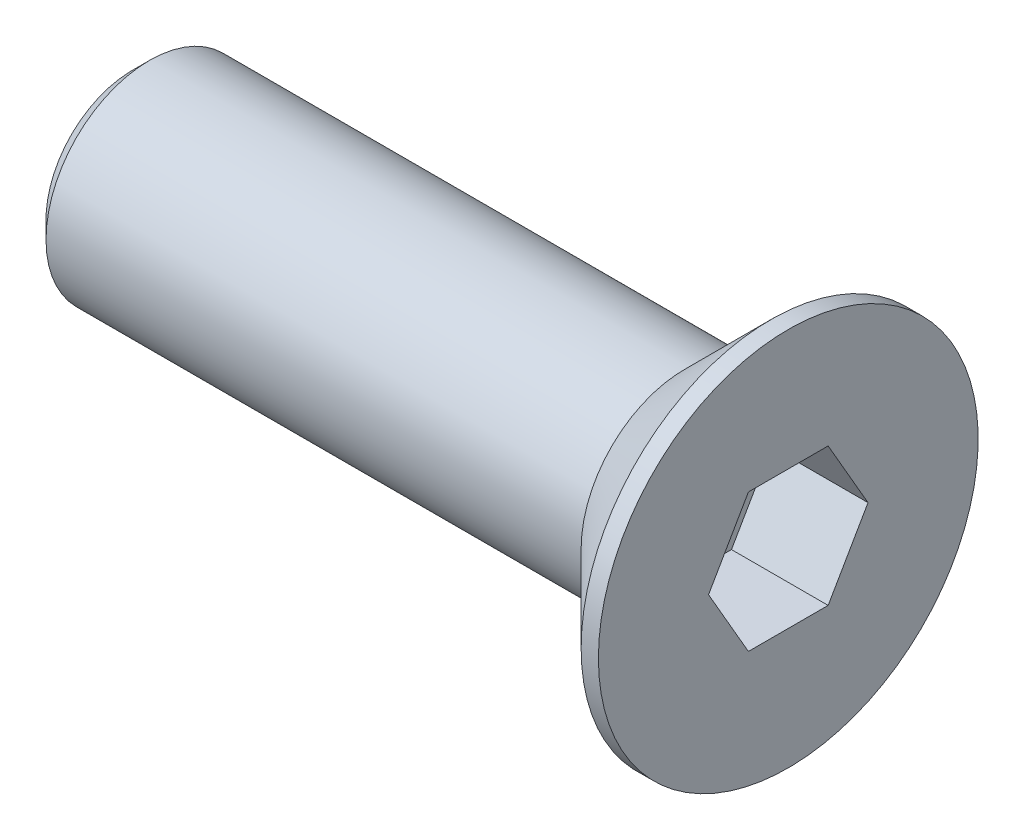
SolidWorks part; units mm, degrees
ref_plane "Plan1" through (0, 0, 0) normal (0, 0, 1) x (1, 0, 0)
ref_plane "Plan2" through (0, 0, 0) normal (0, 1, 0) x (1, 0, 0)
ref_plane "Plan3" through (0, 0, 0) normal (1, 0, 0) x (0, 0, -1)
sketch "Esquisse1" plane through (0, 0, 0) normal (0, 0, 1) x (1, 0, 0)
  line L0 (-25.8285, 0) -> (47.3208, 0) construction
  line L1 (0, 0) -> (0, 3)
  line L2 (0, 3) -> (16, 3)
  line L3 (16, 3) -> (18.5, 5.5)
  line L4 (19, 5.5) -> (19, 0)
  line L5 (19, 0) -> (0, 0)
  line L6 (18.5, 5.5) -> (19, 5.5)
  dimension "D1" = 6
  dimension "D2" = 16
  dimension "D3" = 45
  dimension "D4" = 11
  dimension "D5" = 3
revolve "Base-Révolution" add sketch "Esquisse1" angle 360 about L0
chamfer "Chanfrein2" distance 0.5 angle 45 1 edges at (0, 0, 3)
sketch "Esquisse2" plane through (19, 0, 0) normal (1, 0, 0) x (0, 0, -1)
  line L1 (2.3094, 0) -> (1.1547, 2)
  line L2 (1.1547, 2) -> (-1.1547, 2)
  line L3 (-1.1547, 2) -> (-2.3094, 0)
  line L4 (-2.3094, 0) -> (-1.1547, -2)
  line L5 (-1.1547, -2) -> (1.1547, -2)
  line L6 (1.1547, -2) -> (2.3094, 0)
  circle A0 centre (0, 0) radius 2 construction
  dimension "D1" = 4
extrude "Empreinte pour clé" cut sketch "Esquisse2" against normal blind 2.8
